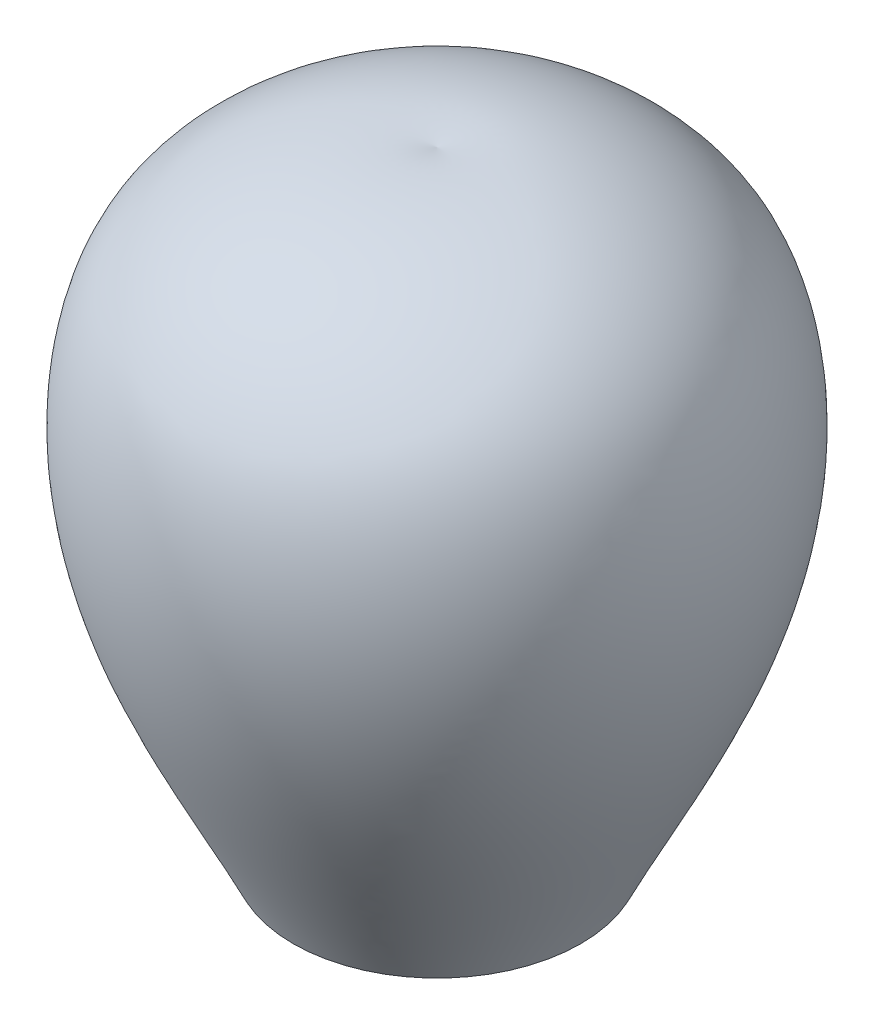
SolidWorks part; units mm, degrees
ref_plane "Front Plane" through (0, 0, 0) normal (0, 0, 1) x (1, 0, 0)
ref_plane "Top Plane" through (0, 0, 0) normal (0, 1, 0) x (1, 0, 0)
ref_plane "Right Plane" through (0, 0, 0) normal (1, 0, 0) x (0, 0, -1)
sketch "Sketch1" plane through (0, 0, 0) normal (0, 0, 1) x (1, 0, 0)
  line L0 (0, 16.3611) -> (0, -7.7674) construction
  line L1 (-5, -7.7674) -> (5, -7.7674)
  spline S0 degree 3 poles (0, 13.7169) (-3.03, 14.2393) (-8.0817, 12.3506) (-9.995, 5.7924) (-8.9256, -0.6631) (-6.2429, -5.1933) (-5, -7.7674) knots 0 0 0 0 0.337006 0.447195 0.698599 1 1 1 1
  spline S1 degree 3 poles (0, 13.7169) (3.03, 14.2393) (8.0817, 12.3506) (9.995, 5.7924) (8.9256, -0.6631) (6.2429, -5.1933) (5, -7.7674) knots 0 0 0 0 0.337006 0.447195 0.698599 1 1 1 1
  dimension "D1" = 10
revolve "Revolve1" add sketch "Sketch1" angle 360 about L0
sketch "Sketch2" plane through (0, -7.7674, 0) normal (0, -1, 0) x (1, 0, 0)
  circle A0 centre (0, 0) radius 2
sketch "Sketch3" plane through (0, -7.7674, 0) normal (0, -1, 0) x (1, 0, 0)
  circle A0 centre (0, 0) radius 1
